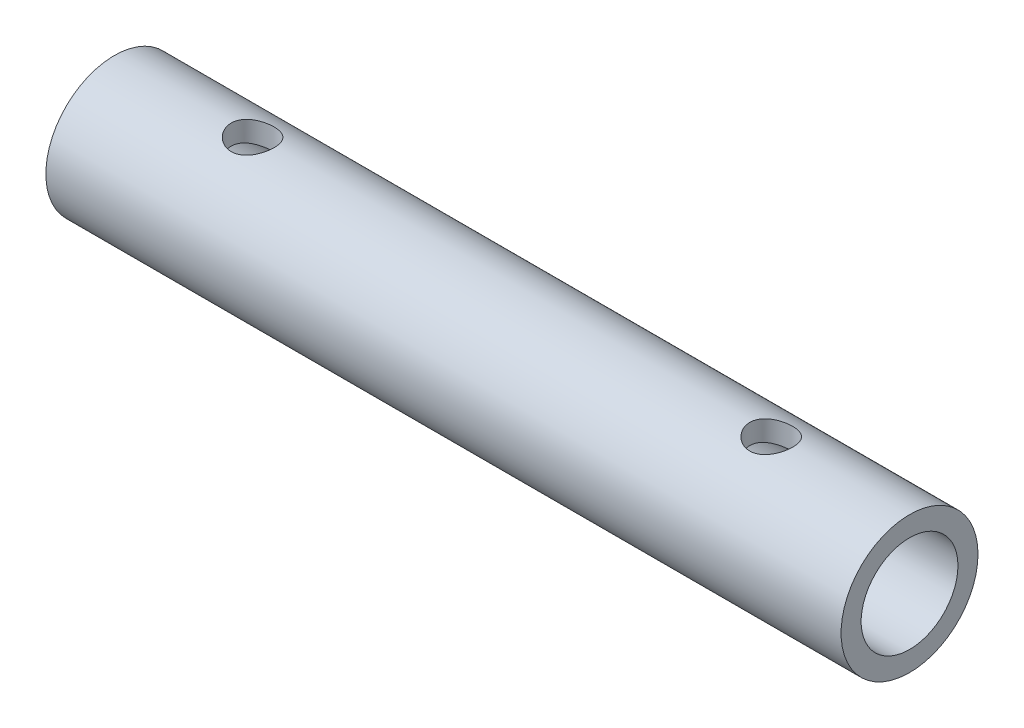
SolidWorks part; units mm, degrees
ref_plane "Front" through (0, 0, 0) normal (0, 0, 1) x (1, 0, 0)
ref_plane "Top" through (0, 0, 0) normal (0, 1, 0) x (1, 0, 0)
ref_plane "Right" through (0, 0, 0) normal (1, 0, 0) x (0, 0, -1)
sketch "草图1" plane through (0, 0, 0) normal (1, 0, 0) x (0, 0, -1)
  circle A0 centre (0, 0) radius 7
  circle A1 centre (0, 0) radius 9.9
extrude "凸台-拉伸1" add sketch "草图1" along normal blind 115
sketch "草图2" plane through (0, 0, 0) normal (0, 1, 0) x (1, 0, 0)
  line L0 (0, 0) -> (20, 0) construction
  line L1 (0, 0) -> (95, 0) construction
  circle A0 centre (20, 0) radius 3.1
  circle A1 centre (95, 0) radius 3.1
extrude "切除-拉伸1" cut sketch "草图2" against normal through all both and the other way through all
